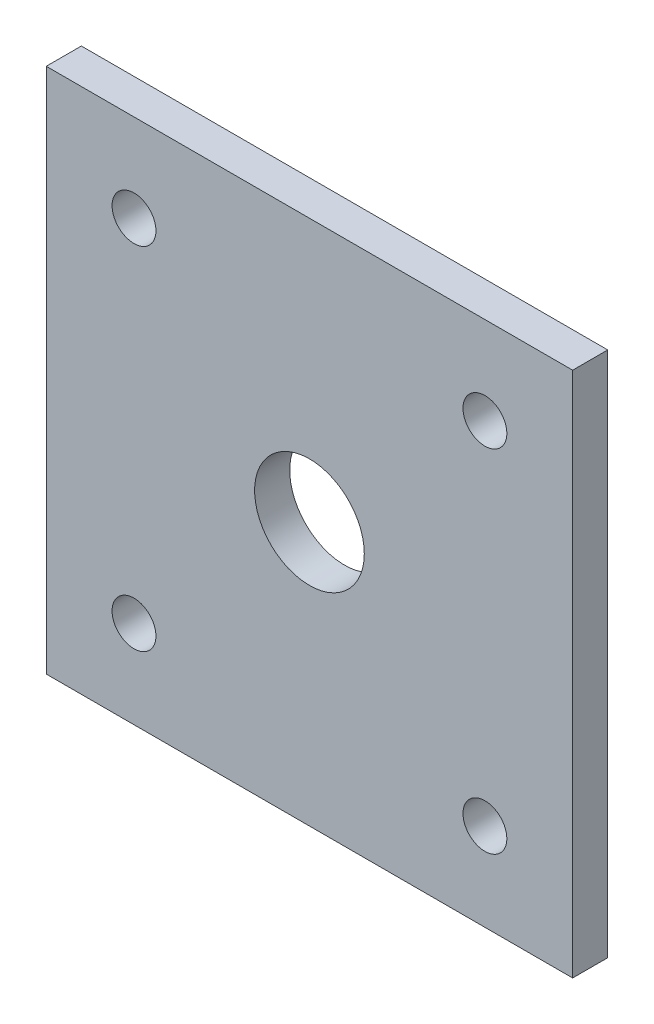
SolidWorks part; units mm, degrees
ref_plane "Front Plane" through (0, 0, 0) normal (0, 0, 1) x (1, 0, 0)
ref_plane "Top Plane" through (0, 0, 0) normal (0, 1, 0) x (1, 0, 0)
ref_plane "Right Plane" through (0, 0, 0) normal (1, 0, 0) x (0, 0, -1)
sketch "Sketch1" plane through (0, 0, 0) normal (0, 0, 1) x (1, 0, 0)
  line L1 (-60, 60) -> (60, 60)
  line L2 (-60, 60) -> (-60, -60)
  line L3 (-60, -60) -> (60, -60)
  line L4 (60, 60) -> (60, -60)
  line L5 (-60, 60) -> (60, -60) construction
  line L6 (-60, -60) -> (60, 60) construction
  point P0 (0, 0)
  dimension "D1" = 120
extrude "Boss-Extrude1" add sketch "Sketch1" along normal blind 8
sketch "Sketch2" plane through (0, 0, 8) normal (0, 0, 1) x (1, 0, 0)
  line L0 (60, 60) -> (-60, 60) construction
  line L1 (-60, 60) -> (-60, -60) construction
  circle A0 centre (-40, 40) radius 5
  dimension "D1" = 10
  dimension "D2" = 20
  dimension "D3" = 20
extrude "Cut-Extrude1" cut sketch "Sketch2" against normal through all
pattern_linear "LPattern1" count 2 spacing 80 along (1, 0, 0) count 2 spacing 80 along (0, -1, 0) of "Cut-Extrude1"
sketch "Sketch3" plane through (0, 0, 8) normal (0, 0, 1) x (1, 0, 0)
  circle A0 centre (0, 0) radius 12.5
  dimension "D1" = 25
extrude "Cut-Extrude2" cut sketch "Sketch3" against normal through all
